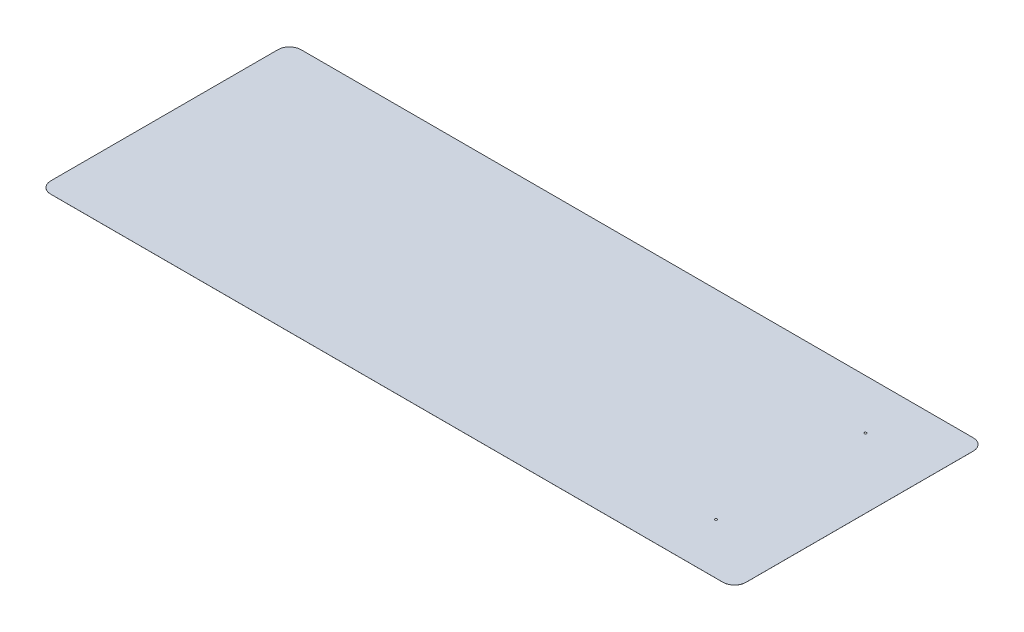
SolidWorks part; units mm, degrees
material "ETFE Film"
ref_plane "Front Plane" through (0, 0, 0) normal (0, 0, 1) x (1, 0, 0)
ref_plane "Top Plane" through (0, 0, 0) normal (0, 1, 0) x (1, 0, 0)
ref_plane "Right Plane" through (0, 0, 0) normal (1, 0, 0) x (0, 0, -1)
sketch "Sketch1" plane through (0, 0, 0) normal (0, 1, 0) x (1, 0, 0)
  line L4 (-920.75, -342.8433) -> (920.75, -342.8433)
  line L5 (952.4433, -311.15) -> (952.4433, 311.15)
  line L6 (920.75, 342.8433) -> (-920.75, 342.8433)
  line L7 (-952.4433, 311.15) -> (-952.4433, -311.15)
  line L8 (-920.75, -342.8433) -> (920.75, -342.8433)
  line L9 (952.4433, -311.15) -> (952.4433, 311.15)
  line L10 (920.75, 342.8433) -> (-920.75, 342.8433)
  line L11 (-952.4433, 311.15) -> (-952.4433, -311.15)
  arc A4 (920.75, -342.8433) -> (952.4433, -311.15) centre (920.75, -311.15) ccw
  arc A5 (952.4433, 311.15) -> (920.75, 342.8433) centre (920.75, 311.15) ccw
  arc A6 (-920.75, 342.8433) -> (-952.4433, 311.15) centre (-920.75, 311.15) ccw
  arc A7 (-952.4433, -311.15) -> (-920.75, -342.8433) centre (-920.75, -311.15) ccw
  arc A8 (920.75, -342.8433) -> (952.4433, -311.15) centre (920.75, -311.15) ccw
  arc A9 (952.4433, 311.15) -> (920.75, 342.8433) centre (920.75, 311.15) ccw
  arc A10 (-920.75, 342.8433) -> (-952.4433, 311.15) centre (-920.75, 311.15) ccw
  arc A11 (-952.4433, -311.15) -> (-920.75, -342.8433) centre (-920.75, -311.15) ccw
  dimension "D1" = 0
extrude "Boss-Extrude1" add sketch "Sketch1" along normal blind 0.127
sketch "Sketch2" plane through (0, 0.127, 0) normal (0, 1, 0) x (1, 0, 0)
  line L0 (762, -339.725) -> (762, 342.8433) construction
  line L1 (920.75, 342.8433) -> (-920.75, 342.8433) construction
  circle A0 centre (762, 206.3296) radius 3.175
  circle A1 centre (762, -203.2113) radius 3.175
  point P13 (762, -203.2113)
  point P14 (762, -66.6977)
  point P15 (762, 69.816)
  point P16 (762, 206.3296)
  dimension "D1" = 6.35
  dimension "D2" = 762
extrude "Cut-Extrude1" cut sketch "Sketch2" against normal through all
